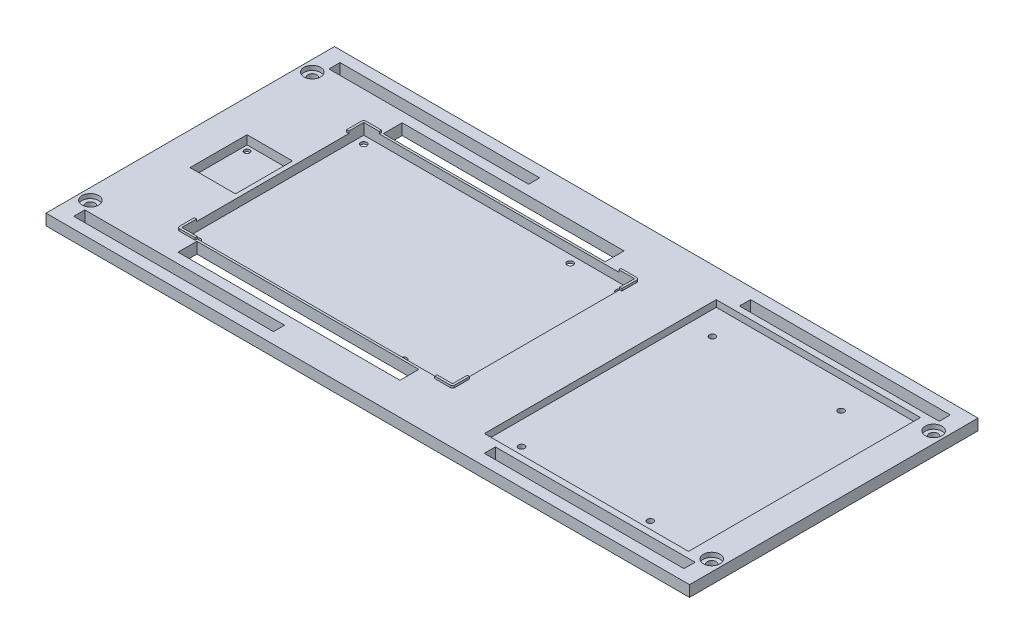
SolidWorks part; units mm, degrees
ref_plane "Alzado" through (0, 0, 0) normal (0, 0, 1) x (1, 0, 0)
ref_plane "Planta" through (0, 0, 0) normal (0, 1, 0) x (1, 0, 0)
ref_plane "Vista lateral" through (0, 0, 0) normal (1, 0, 0) x (0, 0, -1)
sketch "Croquis2" plane through (0, 0, 0) normal (0, 1, 0) x (1, 0, 0)
  line L1 (-145, -65) -> (145, -65)
  line L2 (-145, -65) -> (-145, 65)
  line L3 (-145, 65) -> (145, 65)
  line L4 (145, -65) -> (145, 65)
  line L5 (-145, -65) -> (145, 65) construction
  line L6 (-145, 65) -> (145, -65) construction
  point P0 (0, 0)
  dimension "D1" = 130
  dimension "D2" = 290
extrude "Saliente-Extruir1" add sketch "Croquis2" along normal blind 5
sketch "Croquis3" plane through (0, 5, 0) normal (0, 1, 0) x (1, 0, 0)
  line L0 (0, -65) -> (0, -60) construction
  line L1 (-145, -65) -> (145, -65) construction
  line L2 (0, -60) -> (-47.5, -60) construction
  line L3 (0, -60) -> (47.5, -60) construction
  line L4 (47.5, -55) -> (137.5, -55)
  line L5 (-47.5, -60) -> (-137.5, -60)
  line L6 (-47.5, -60) -> (-47.5, -55)
  line L7 (-47.5, -55) -> (-137.5, -55)
  line L8 (-137.5, -60) -> (-137.5, -55)
  line L9 (137.5, -60) -> (137.5, -55)
  line L10 (47.5, -60) -> (137.5, -60)
  line L11 (47.5, -60) -> (47.5, -55)
  line L12 (-2.75, 0) -> (2.75, 0) construction
  line L13 (47.5, 60) -> (47.5, 55)
  line L14 (47.5, 60) -> (137.5, 60)
  line L15 (137.5, 60) -> (137.5, 55)
  line L16 (47.5, 55) -> (137.5, 55)
  line L17 (-47.5, 55) -> (-137.5, 55)
  line L18 (-137.5, 60) -> (-137.5, 55)
  line L19 (-47.5, 60) -> (-137.5, 60)
  line L20 (-47.5, 60) -> (-47.5, 55)
  dimension "D1" = 47.5
  dimension "D2" = 5
  dimension "D3" = 5
  dimension "D4" = 90
extrude "Cortar-Extruir1" cut sketch "Croquis3" against normal through all
sketch "Croquis4" plane through (0, 5, 0) normal (0, 1, 0) x (1, 0, 0)
  line L0 (-137.5, 55) -> (-137.5, 10.9) construction
  line L1 (-137.5, 10.9) -> (-130.3, 10.9) construction
  line L3 (-130.3, 10.9) -> (-109.8, 10.9)
  line L4 (-130.3, 10.9) -> (-130.3, -14.8)
  line L5 (-130.3, -14.8) -> (-109.8, -14.8)
  line L6 (-109.8, 10.9) -> (-109.8, -14.8)
  dimension "D1" = 44.1
  dimension "D2" = 7.2
  dimension "D3" = 20.5
  dimension "D4" = 25.7
extrude "Cortar-Extruir2" cut sketch "Croquis4" against normal blind 4
sketch "Croquis5" plane through (0, 1, 0) normal (0, 1, 0) x (1, 0, 0)
  line L0 (-120.05, 10.9) -> (-120.05, -14.8) construction
  line L1 (-130.3, 10.9) -> (-127.8, 10.9) construction
  line L2 (-130.3, 10.9) -> (-130.3, 8.4) construction
  line L3 (-130.3, 8.4) -> (-127.8, 8.4) construction
  line L4 (-127.8, 10.9) -> (-127.8, 8.4) construction
  line L5 (-109.8, 10.9) -> (-130.3, 10.9) construction
  line L6 (-130.3, -14.8) -> (-109.8, -14.8) construction
  line L7 (-130.3, -1.95) -> (-109.8, -1.95) construction
  line L8 (-130.3, 10.9) -> (-130.3, -14.8) construction
  line L9 (-109.8, -14.8) -> (-109.8, 10.9) construction
  circle A0 centre (-127.8, 8.4) radius 1.25
  circle A1 centre (-112.3, 8.4) radius 1.25
  circle A2 centre (-112.3, -12.3) radius 1.25
  circle A3 centre (-127.8, -12.3) radius 1.25
  dimension "D3" = 2.5
  dimension "D1" = 2.5
  dimension "D2" = 2.5
extrude "Cortar-Extruir3" cut sketch "Croquis5" against normal blind 4
sketch "Croquis6" plane through (0, 5, 0) normal (0, 1, 0) x (1, 0, 0)
  line L0 (137.5, 55) -> (137.5, 52.25) construction
  line L1 (137.5, 52.25) -> (131.8, 52.25) construction
  line L3 (131.8, 52.25) -> (39.8, 52.25)
  line L4 (131.8, 52.25) -> (131.8, -52.25)
  line L5 (131.8, -52.25) -> (39.8, -52.25)
  line L6 (39.8, 52.25) -> (39.8, -52.25)
  dimension "D1" = 2.75
  dimension "D2" = 5.7
  dimension "D3" = 92
  dimension "D4" = 104.5
extrude "Cortar-Extruir4" cut sketch "Croquis6" against normal blind 3 contours L4 L3 L6 L5
sketch "Croquis7" plane through (0, 5, 0) normal (0, 1, 0) x (1, 0, 0)
  line L0 (-50, -52) -> (-50, -40.5) construction
  line L1 (-145, -65) -> (-50, -65) construction
  line L2 (-145, -65) -> (-145, -52) construction
  line L3 (-145, -52) -> (-50, -52) construction
  line L4 (-50, -65) -> (-50, -52) construction
  line L5 (-2.75, 0) -> (2.75, 0) construction
  line L6 (-100, -42) -> (0, -42)
  line L7 (-100, -42) -> (-100, -50.5)
  line L8 (-100, -50.5) -> (0, -50.5)
  line L9 (0, -42) -> (0, -50.5)
  line L10 (-100, -42) -> (0, -50.5) construction
  line L11 (-100, -50.5) -> (0, -42) construction
  line L12 (-100, 50.5) -> (0, 50.5)
  line L13 (0, 42) -> (0, 50.5)
  line L14 (-100, 42) -> (0, 42)
  line L15 (-100, 42) -> (-100, 50.5)
  line L16 (-47.5, -55) -> (-137.5, -55) construction
  point P5 (-50, -46.25)
  dimension "D1" = 13
  dimension "D2" = 95
  dimension "D3" = 8.5
  dimension "D4" = 100
  dimension "D5" = 4.5
extrude "Cortar-Extruir5" cut sketch "Croquis7" against normal through all
sketch "Croquis8" plane through (0, 5, 0) normal (0, 1, 0) x (1, 0, 0)
  line L0 (-145, 0) -> (145, 0) construction
  line L1 (-145, 65) -> (-145, -65) construction
  line L2 (145, -65) -> (145, 65) construction
  line L3 (0, 0) -> (0, 50) construction
  line L4 (0, -2.75) -> (0, 2.75) construction
  line L5 (0, 50) -> (-140, 50) construction
  line L6 (0, 50) -> (0, 0) construction
  line L7 (0, 0) -> (-140, 0) construction
  line L8 (-140, 50) -> (-140, 0) construction
  circle A0 centre (-140, 50) radius 2
  circle A1 centre (140, 50) radius 2
  circle A2 centre (140, -50) radius 2
  circle A3 centre (-140, -50) radius 2
  dimension "D3" = 4
  dimension "D1" = 50
  dimension "D2" = 140
extrude "Cortar-Extruir6" cut sketch "Croquis8" against normal through all
sketch "Croquis9" plane through (0, 5, 0) normal (0, 1, 0) x (1, 0, 0)
  line L0 (-2.75, 0) -> (2.75, 0) construction
  line L1 (0, -2.75) -> (0, 2.75) construction
  circle A0 centre (-140, 50) radius 3.75
  circle A1 centre (-140, -50) radius 3.75
  circle A2 centre (140, -50) radius 3.75
  circle A3 centre (140, 50) radius 3.75
  dimension "D1" = 7.5
extrude "Cortar-Extruir7" cut sketch "Croquis9" against normal blind 2
sketch "Croquis10" plane through (0, 5, 0) normal (0, 1, 0) x (1, 0, 0)
  line L0 (-109.8, -14.8) -> (-109.8, 10.9) construction
  line L1 (-100, 42) -> (0, 42) construction
  line L2 (0, -42) -> (-100, -42) construction
  line L4 (-107.8, -41) -> (14.2, -41)
  line L5 (-107.8, -41) -> (-107.8, 41)
  line L6 (-107.8, 41) -> (14.2, 41)
  line L7 (14.2, -41) -> (14.2, 41)
  line L8 (-107.8, -41) -> (14.2, 41) construction
  line L9 (-107.8, 41) -> (14.2, -41) construction
  point P6 (-46.8, 0)
  dimension "D1" = 122
  dimension "D2" = 1
  dimension "D3" = 2
  dimension "D4" = 1
extrude "Cortar-Extruir8" cut sketch "Croquis10" against normal blind 4
sketch "Croquis13" plane through (0, 1, 0) normal (0, 1, 0) x (1, 0, 0)
  line L0 (-46.8, 41) -> (-46.8, -41) construction
  line L1 (-107.8, 41) -> (-104.3, 41) construction
  line L2 (-107.8, 41) -> (-107.8, 37.5) construction
  line L3 (-107.8, 37.5) -> (-104.3, 37.5) construction
  line L4 (-104.3, 41) -> (-104.3, 37.5) construction
  line L5 (14.2, 41) -> (-107.8, 41) construction
  line L6 (-107.8, -41) -> (14.2, -41) construction
  line L7 (-107.8, 0) -> (14.2, 0) construction
  line L8 (-107.8, 41) -> (-107.8, -41) construction
  line L9 (14.2, -41) -> (14.2, 41) construction
  circle A0 centre (-104.3, 37.5) radius 1.4
  circle A1 centre (10.7, 37.5) radius 1.4
  circle A2 centre (10.7, -37.5) radius 1.4
  circle A3 centre (-104.3, -37.5) radius 1.4
  dimension "D3" = 2.8
  dimension "D1" = 3.5
  dimension "D2" = 3.5
extrude "Cortar-Extruir9" cut sketch "Croquis13" against normal blind 3
sketch "Croquis14" plane through (0, 1, 0) normal (0, 1, 0) x (1, 0, 0)
  line L0 (-107.8, 41) -> (-7.8, 41) construction
  line L1 (14.2, 41) -> (-107.8, 41) construction
  line L2 (-7.8, 41) -> (-7.8, -41) construction
  line L3 (-107.8, -41) -> (14.2, -41) construction
  line L4 (-57.8, 41) -> (-57.8, -41) construction
  circle A0 centre (-104.3, -37.5) radius 1.4 construction
  circle A1 centre (-104.3, 37.5) radius 1.4 construction
  circle A2 centre (-104.3, -37.5) radius 1.4
  circle A3 centre (-104.3, 37.5) radius 1.4
  circle A4 centre (-11.3, 37.5) radius 1.4
  circle A5 centre (-11.3, -37.5) radius 1.4
extrude "Cortar-Extruir10" cut sketch "Croquis14" against normal blind 3
sketch "Croquis15" plane through (0, 5, 0) normal (0, 1, 0) x (1, 0, 0)
  line L0 (-107.8, 41) -> (-107.8, -41) construction
  line L1 (-107.8, 42) -> (-100.7839, 42)
  line L2 (-108.8, 41) -> (-108.8, 34.3184)
  line L3 (-108.8, 34.3184) -> (-107.8, 34.3184)
  line L4 (-100.7839, 42) -> (-100.7839, 41)
  line L5 (14.2, 41) -> (-107.8, 41) construction
  line L6 (-107.8, 41) -> (-107.8, 34.3184)
  line L7 (-107.8, 41) -> (-100.7839, 41)
  line L8 (-46.8, 41) -> (-46.8, -41) construction
  line L9 (-107.8, -41) -> (14.2, -41) construction
  line L10 (-107.8, 0) -> (14.2, 0) construction
  line L11 (14.2, -41) -> (14.2, 41) construction
  line L12 (15.2, 41) -> (15.2, 34.3184)
  line L13 (15.2, 34.3184) -> (14.2, 34.3184)
  line L14 (14.2, 41) -> (14.2, 34.3184)
  line L15 (14.2, 41) -> (7.1839, 41)
  line L16 (7.1839, 42) -> (7.1839, 41)
  line L17 (14.2, 42) -> (7.1839, 42)
  line L18 (14.2, -42) -> (7.1839, -42)
  line L19 (7.1839, -42) -> (7.1839, -41)
  line L20 (14.2, -41) -> (7.1839, -41)
  line L21 (14.2, -41) -> (14.2, -34.3184)
  line L22 (15.2, -34.3184) -> (14.2, -34.3184)
  line L23 (15.2, -41) -> (15.2, -34.3184)
  line L24 (-108.8, -41) -> (-108.8, -34.3184)
  line L25 (-108.8, -34.3184) -> (-107.8, -34.3184)
  line L26 (-107.8, -41) -> (-107.8, -34.3184)
  line L27 (-107.8, -41) -> (-100.7839, -41)
  line L28 (-100.7839, -42) -> (-100.7839, -41)
  line L29 (-107.8, -42) -> (-100.7839, -42)
  arc A0 (-107.8, 42) -> (-108.8, 41) centre (-107.8, 41) ccw
  arc A1 (14.2, 42) -> (15.2, 41) centre (14.2, 41) cw
  arc A2 (14.2, -42) -> (15.2, -41) centre (14.2, -41) ccw
  arc A3 (-107.8, -42) -> (-108.8, -41) centre (-107.8, -41) cw
  dimension "D3" = 1
  dimension "D1" = 1
  dimension "D2" = 1
extrude "Saliente-Extruir2" add sketch "Croquis15" along normal blind 1
sketch "Croquis16" plane through (0, 2, 0) normal (0, 1, 0) x (1, 0, 0)
  line L0 (85.8, 52.25) -> (85.8, -52.25) construction
  line L1 (131.8, 52.25) -> (39.8, 52.25) construction
  line L2 (131.8, -52.25) -> (39.8, -52.25) construction
  line L3 (50.3, 50) -> (50.3, 40) construction
  line L4 (46.3, -50) -> (125.3, -50) construction
  line L5 (46.3, -50) -> (46.3, 50) construction
  line L6 (46.3, 50) -> (125.3, 50) construction
  line L7 (125.3, -50) -> (125.3, 50) construction
  line L8 (46.3, -50) -> (125.3, 50) construction
  line L9 (46.3, 50) -> (125.3, -50) construction
  line L10 (50.3, -50) -> (50.3, -46) construction
  line L11 (125.3, 40) -> (108.3, 40) construction
  line L12 (125.3, -46) -> (108.3, -46) construction
  circle A0 centre (50.3, 40) radius 1.375
  circle A1 centre (50.3, -46) radius 1.375
  circle A2 centre (108.3, 40) radius 1.375
  circle A3 centre (108.3, -46) radius 1.375
  point P6 (85.8, 0)
  dimension "D5" = 2.75
  dimension "D8" = 2.75
  dimension "D11" = 2.75
  dimension "D14" = 2.75
  dimension "D1" = 79
  dimension "D2" = 100
  dimension "D3" = 4
  dimension "D4" = 10
  dimension "D6" = 4
  dimension "D7" = 4
  dimension "D9" = 17
  dimension "D10" = 10
  dimension "D12" = 17
  dimension "D13" = 4
extrude "Cortar-Extruir11" cut sketch "Croquis16" against normal through all
